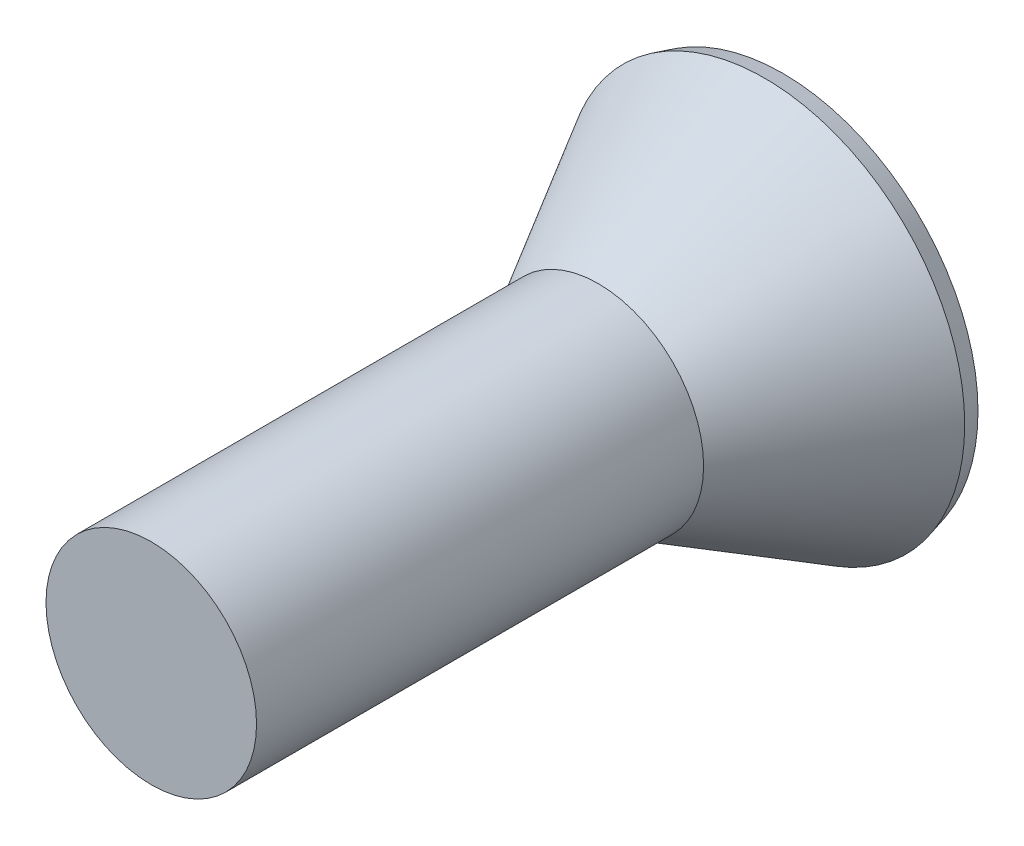
SolidWorks part; units mm, degrees
ref_plane "前视基准面" through (0, 0, 0) normal (0, 0, 1) x (1, 0, 0)
ref_plane "上视基准面" through (0, 0, 0) normal (0, 1, 0) x (1, 0, 0)
ref_plane "右视基准面" through (0, 0, 0) normal (1, 0, 0) x (0, 0, -1)
sketch "草图1" plane through (0, 0, 0) normal (0, 1, 0) x (1, 0, 0)
  line L0 (-2.0085, -0.0038) -> (-0.0085, -0.0038)
  line L1 (-0.0085, -1.7571) -> (-0.0085, -0.0038) construction
  line L2 (-0.0085, -1.7571) -> (-1.0085, -1.7571) construction
  line L4 (-1.0085, -1.7571) -> (-2.0085, -0.0038)
  line L5 (-0.0085, -0.0038) -> (-0.0085, -6.0038)
  line L6 (-1.0085, -1.7571) -> (-0.0085, -1.7571) construction
  line L7 (-1.0085, -1.7571) -> (-1.0085, -6.0038)
  line L8 (-1.0085, -6.0038) -> (-0.0085, -6.0038)
  dimension "D1" = 1.7533
  dimension "D2" = 6
  dimension "D3" = 1
  dimension "D4" = 2
  dimension "D5" = 1
revolve "旋转5" add sketch "草图1" angle 360 about L5
sketch "草图2" plane through (0, 0, 0.0038) normal (0, 0, 1) x (1, 0, 0)
  line L7 (0.8575, 0) -> (0.4245, 0.75)
  line L8 (0.4245, 0.75) -> (-0.4415, 0.75)
  line L9 (-0.4415, 0.75) -> (-0.8745, 0)
  line L10 (-0.8745, 0) -> (-0.4415, -0.75)
  line L11 (-0.4415, -0.75) -> (0.4245, -0.75)
  line L12 (0.4245, -0.75) -> (0.8575, 0)
  circle A0 centre (-0.0085, 0) radius 0.75 construction
  dimension "D1" = 1.5
extrude "切除-拉伸1" cut sketch "草图2" along normal blind 1.5
chamfer "倒角1" distance 0.2 angle 45 1 edges at (-2.0085, 0, 0.0038)
